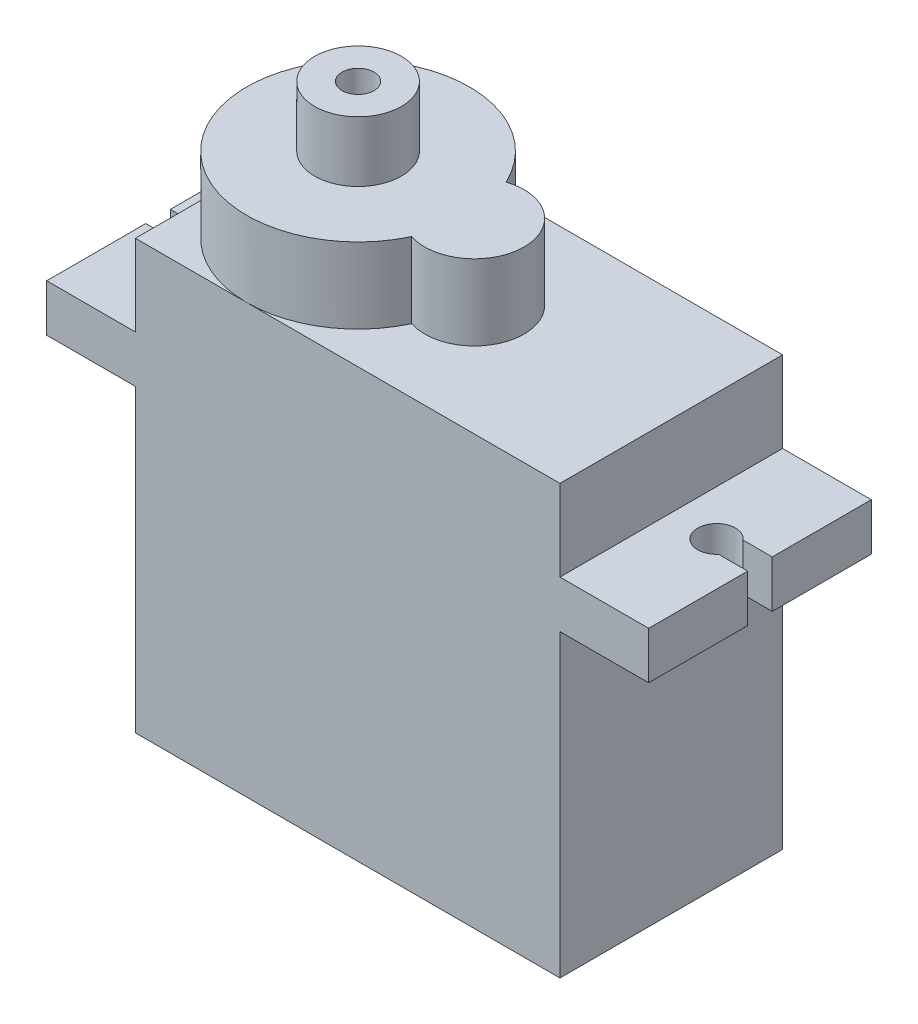
SolidWorks part; units mm, degrees
ref_plane "Plano frontal" through (0, 0, 0) normal (0, 0, 1) x (1, 0, 0)
ref_plane "Plano superior" through (0, 0, 0) normal (0, 1, 0) x (1, 0, 0)
ref_plane "Plano direito" through (0, 0, 0) normal (1, 0, 0) x (0, 0, -1)
sketch "Esboço1" plane through (0, 0, 0) normal (0, 1, 0) x (1, 0, 0)
  line L0 (0, 0) -> (22.5, 0)
  line L1 (22.5, 0) -> (22.5, 11.8)
  line L2 (22.5, 11.8) -> (0, 11.8)
  line L3 (0, 11.8) -> (0, 0)
extrude "Ressalto-extrusão1" add sketch "Esboço1" along normal blind 22.7
sketch "Esboço2" plane through (0, 0, 0) normal (-1, 0, 0) x (0, 0, 1)
  line L2 (-11.8, 15.9) -> (0, 15.9)
  line L3 (-11.8, 22.7) -> (-11.8, 0) construction
  line L4 (0, 22.7) -> (0, 0) construction
  line L5 (0, 15.9) -> (0, 18.4)
  line L6 (0, 18.4) -> (-11.8, 18.4)
  line L7 (-11.8, 18.4) -> (-11.8, 15.9)
extrude "Ressalto-extrusão2" add sketch "Esboço2" along normal blind 4.7
sketch "Esboço3" plane through (22.5, 0, 0) normal (1, 0, 0) x (0, 0, -1)
  line L2 (5.9, 15.9) -> (11.8, 15.9)
  line L3 (11.8, 22.7) -> (11.8, 0) construction
  line L4 (11.8, 15.9) -> (11.8, 18.4)
  line L5 (11.8, 18.4) -> (0, 18.4)
  line L6 (0, 22.7) -> (0, 0) construction
  line L7 (0, 18.4) -> (0, 15.9)
  line L8 (0, 15.9) -> (5.9, 15.9)
extrude "Ressalto-extrusão3" add sketch "Esboço3" along normal blind 4.7
sketch "Esboço4" plane through (0, 22.7, 0) normal (0, 1, 0) x (1, 0, 0)
  arc A0 (11.2442, 8.4) -> (11.2442, 3.4) centre (5.9, 5.9) ccw
  arc A1 (11.2442, 8.4) -> (11.2442, 3.4) centre (12.0678, 5.9) cw
extrude "Ressalto-extrusão4" add sketch "Esboço4" along normal blind 4
sketch "Esboço5" plane through (0, 26.7, 0) normal (0, 1, 0) x (1, 0, 0)
  circle A0 centre (5.9, 5.9) radius 2.3
  circle A1 centre (5.9, 5.9) radius 0.85
extrude "Ressalto-extrusão5" add sketch "Esboço5" along normal blind 3.2
sketch "Esboço6" plane through (0, 18.4, 0) normal (0, 1, 0) x (1, 0, 0)
  line L1 (-4.7, 0) -> (-4.7, 11.8) construction
  line L5 (-4.7, 6.55) -> (-3.1599, 6.55)
  line L6 (-4.7, 5.25) -> (-3.1599, 5.25)
  arc A0 (-3.1599, 5.25) -> (-3.1599, 6.55) centre (-2.4, 5.9) ccw
extrude "Corte-extrusão1" cut sketch "Esboço6" against normal blind 3.2 and the other way through all
sketch "Esboço7" plane through (0, 18.4, 0) normal (0, 1, 0) x (1, 0, 0)
  line L1 (27.2, 11.8) -> (27.2, 0) construction
  line L4 (27.2, 5.25) -> (25.6599, 5.25)
  line L5 (27.2, 6.55) -> (25.6599, 6.55)
  arc A0 (25.6599, 6.55) -> (25.6599, 5.25) centre (24.9, 5.9) ccw
extrude "Corte-extrusão2" cut sketch "Esboço7" against normal blind 3.2 and the other way through all
